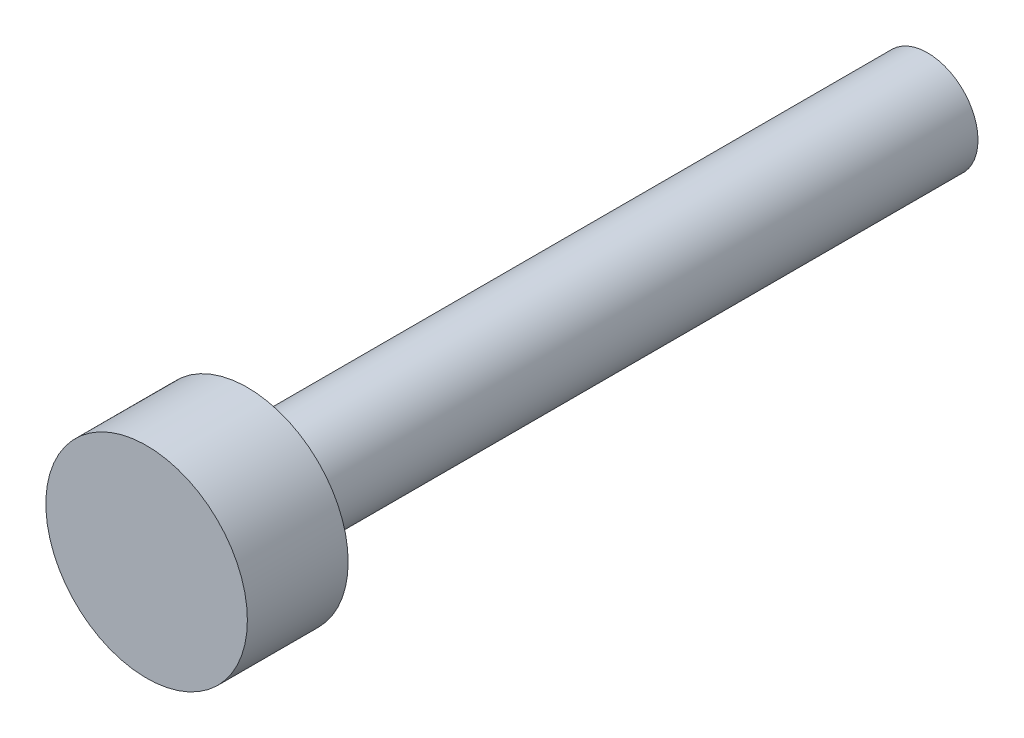
SolidWorks part; units mm, degrees
material "SKD11淬火HRC56-60"
ref_plane "前基準面" through (0, 0, 0) normal (0, 0, 1) x (1, 0, 0)
ref_plane "上基準面" through (0, 0, 0) normal (0, 1, 0) x (1, 0, 0)
ref_plane "右基準面" through (0, 0, 0) normal (1, 0, 0) x (0, 0, -1)
sketch "草图1" plane through (0, 0, 0) normal (0, 0, 1) x (1, 0, 0)
  circle A0 centre (0, 0) radius 2
  dimension "D1" = 4
extrude "凸台-拉伸1" add sketch "草图1" along normal blind 27
sketch "草图2" plane through (0, 0, 27) normal (0, 0, 1) x (1, 0, 0)
  circle A0 centre (0, 0) radius 4
  dimension "D1" = 8
extrude "凸台-拉伸2" add sketch "草图2" along normal blind 4
